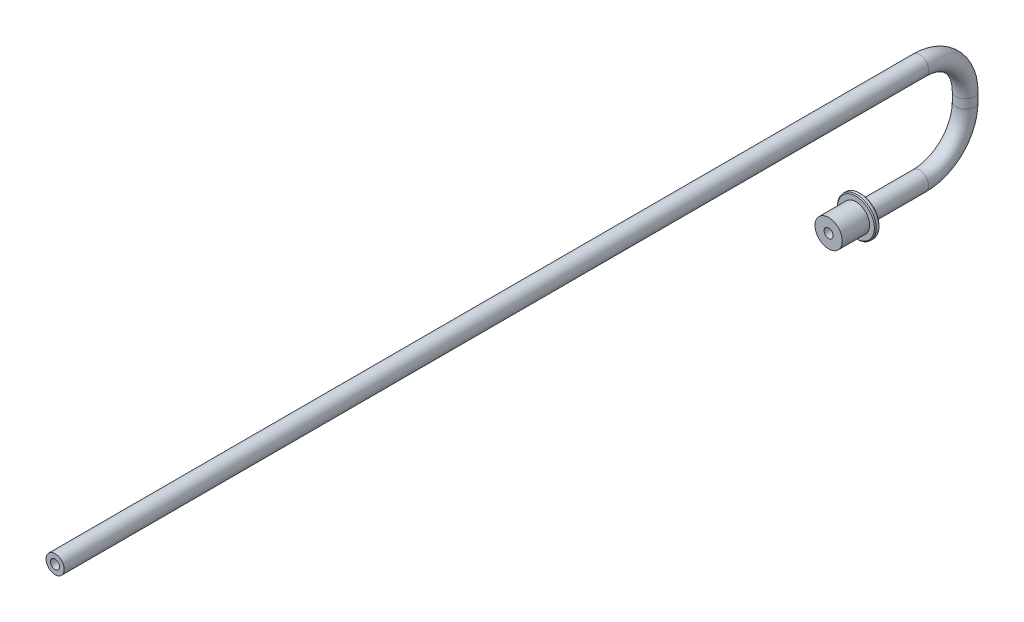
SolidWorks part; units mm, degrees
material "Chrome Stainless Steel"
ref_plane "Front Plane" through (0, 0, 0) normal (0, 0, 1) x (1, 0, 0)
ref_plane "Top Plane" through (0, 0, 0) normal (0, 1, 0) x (1, 0, 0)
ref_plane "Right Plane" through (0, 0, 0) normal (1, 0, 0) x (0, 0, -1)
sketch "Sketch1" plane through (0, 0, 0) normal (0, 0, 1) x (1, 0, 0)
  circle A0 centre (0, 0) radius 4.25
  dimension "D1" = 8.5
extrude "Boss-Extrude1" add sketch "Sketch1" along normal blind 1
sketch "Sketch2" plane through (0, 0, 1) normal (0, 0, 1) x (1, 0, 0)
  circle A0 centre (0, 0) radius 3
  dimension "D1" = 6
extrude "Boss-Extrude2" add sketch "Sketch2" along normal blind 6
sketch "Sketch3" plane through (0, 0, 0) normal (0, 0, -1) x (-1, 0, 0)
  circle A0 centre (0, 0) radius 2
  dimension "D1" = 4
extrude "Cut-Extrude1" cut sketch "Sketch3" against normal through all
chamfer "Chamfer1" distance 0.2 angle 45 3 edges at (-2, 0, 0) (4.25, 0, 1) (4.25, 0, 0)
sketch "Sketch4" plane through (0, 0, 7) normal (0, 0, 1) x (1, 0, 0)
  circle A0 centre (0, 0) radius 2
  circle A1 centre (0, 0) radius 1
  dimension "D1" = 4
  dimension "D2" = 2
sketch "Sketch5" plane through (0, 0, 0) normal (1, 0, 0) x (0, 0, -1)
  line L0 (-7, 0) -> (13, 0)
  line L1 (-7, 1) -> (-7, -1) construction
  line L2 (23, 10) -> (23, 12)
  line L3 (13, 22) -> (-177, 22)
  arc A0 (23, 12) -> (13, 22) centre (13, 12) ccw
  arc A1 (13, 0) -> (23, 10) centre (13, 10) ccw
  point P9 (23, 22)
  point P12 (23, 0)
  dimension "D4" = 10
  dimension "D1" = 30
  dimension "D2" = 22
  dimension "D3" = 200
sweep "Sweep1" add profiles "Sketch4" path "Sketch5"
